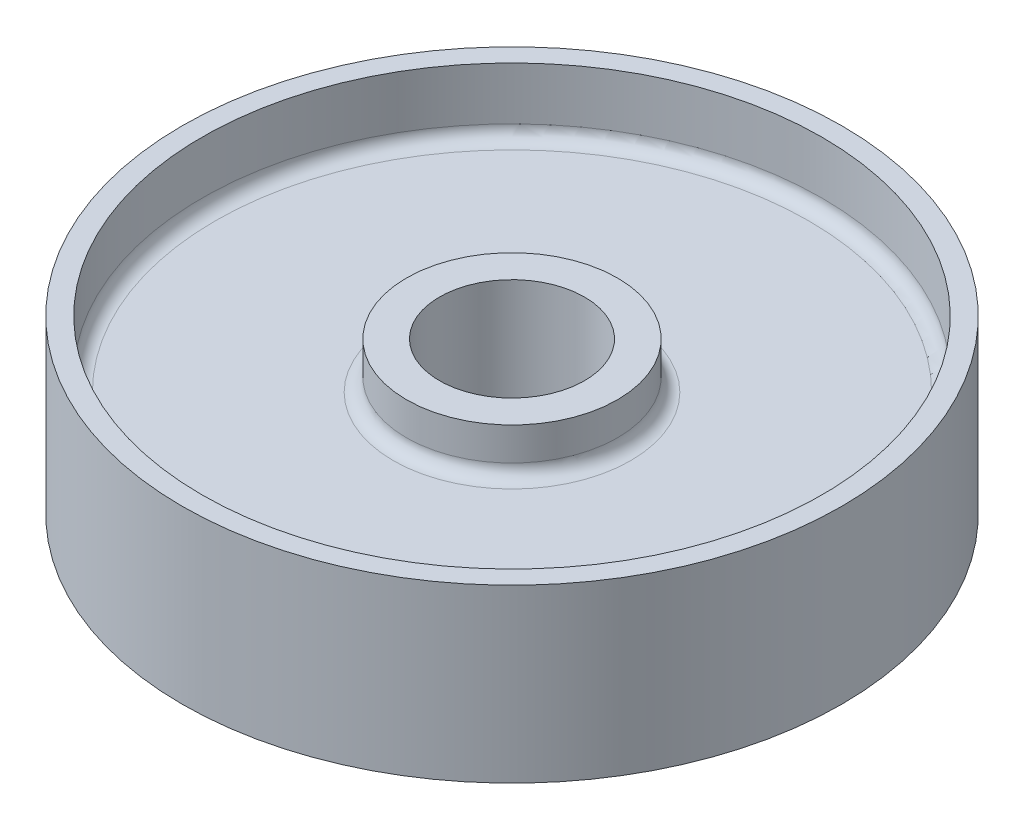
SolidWorks part; units mm, degrees
material "Stainless Steel (ferritic)"
ref_plane "Front Plane" through (0, 0, 0) normal (0, 0, 1) x (1, 0, 0)
ref_plane "Top Plane" through (0, 0, 0) normal (0, 1, 0) x (1, 0, 0)
ref_plane "Right Plane" through (0, 0, 0) normal (1, 0, 0) x (0, 0, -1)
sketch "Sketch1" plane through (0, 0, 0) normal (1, 0, 0) x (0, 0, -1)
  line L0 (0, 0) -> (0, 53.2718) construction
  line L1 (0, 0) -> (50, 0) construction
  line L2 (11, -10) -> (11, 10)
  line L3 (11, 10) -> (16, 10)
  line L4 (16, 10) -> (16, 5)
  line L5 (18, 3) -> (45, 3)
  line L6 (47, 5) -> (47, 13)
  line L7 (47, 13) -> (50, 13)
  line L8 (50, 13) -> (50, -13)
  line L9 (47, -13) -> (50, -13)
  line L10 (47, -5) -> (47, -13)
  line L11 (18, -3) -> (45, -3)
  line L12 (16, -10) -> (16, -5)
  line L13 (11, -10) -> (16, -10)
  arc A0 (45, 3) -> (47, 5) centre (45, 5) ccw
  arc A1 (16, 5) -> (18, 3) centre (18, 5) ccw
  arc A2 (16, -5) -> (18, -3) centre (18, -5) cw
  arc A3 (45, -3) -> (47, -5) centre (45, -5) cw
  point P28 (11, 0)
  dimension "D7" = 2
  dimension "D1" = 100
  dimension "D2" = 94
  dimension "D3" = 26
  dimension "D4" = 20
  dimension "D5" = 22
  dimension "D6" = 32
  dimension "D8" = 6
revolve "Revolve1" add sketch "Sketch1" angle 360 about L0
